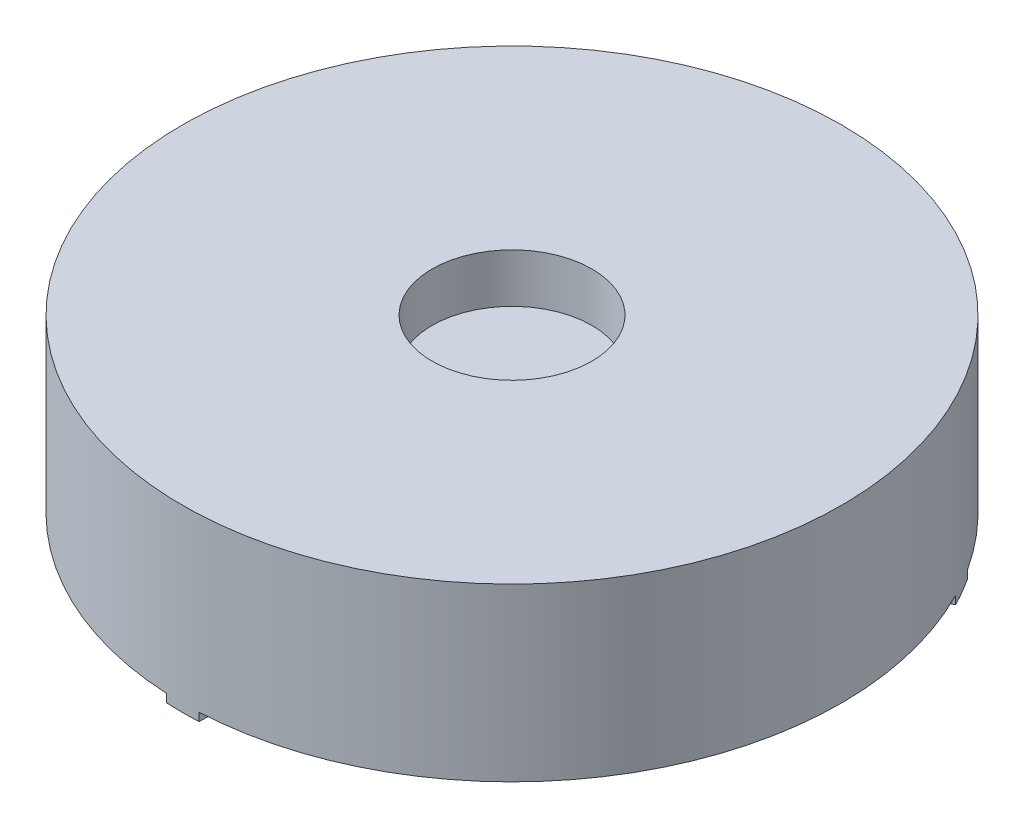
SolidWorks part; units mm, degrees
ref_plane "Front Plane" through (0, 0, 0) normal (0, 0, 1) x (1, 0, 0)
ref_plane "Top Plane" through (0, 0, 0) normal (0, 1, 0) x (1, 0, 0)
ref_plane "Right Plane" through (0, 0, 0) normal (1, 0, 0) x (0, 0, -1)
sketch "Sketch1" plane through (0, 0, 0) normal (1, 0, 0) x (0, 0, -1)
  line L2 (20.2, 10.5) -> (20.2, 0)
  line L3 (20.2, 0) -> (0, 0)
  line L4 (0, 0) -> (0, 7.5)
  line L5 (0, 7.5) -> (4.9, 7.5)
  line L6 (4.9, 7.5) -> (4.9, 10.5)
  line L7 (4.9, 10.5) -> (20.2, 10.5)
  dimension "D1" = 20.2
  dimension "D2" = 10.5
  dimension "D3" = 4.9
  dimension "D4" = 3
revolve "Revolve1" add sketch "Sketch1" angle 360 about L4
sketch "Sketch2" plane through (0, 0, 0) normal (0, -1, 0) x (1, 0, 0)
  line L0 (-1, 20.1752) -> (-1, 19.1739)
  line L1 (1, 20.1752) -> (1, 19.1739)
  line L2 (17.9723, -9.2216) -> (17.1051, -8.7209)
  line L3 (16.9723, -10.9536) -> (16.1051, -10.453)
  line L4 (-16.9723, -10.9536) -> (-16.1051, -10.453)
  line L5 (-17.9723, -9.2216) -> (-17.1051, -8.7209)
  arc A0 (1, 19.1739) -> (-1, 19.1739) centre (0, 0) ccw
  circle A1 centre (0, 0) radius 20.2
  arc A2 (1, 20.1752) -> (-1, 20.1752) centre (0, 0) ccw
  circle A3 centre (0, 0) radius 20.2 construction
  arc A4 (16.9723, -10.9536) -> (17.9723, -9.2216) centre (0, 0) ccw
  arc A5 (16.1051, -10.453) -> (17.1051, -8.7209) centre (0, 0) ccw
  arc A6 (-17.9723, -9.2216) -> (-16.9723, -10.9536) centre (0, 0) ccw
  arc A7 (-17.1051, -8.7209) -> (-16.1051, -10.453) centre (0, 0) ccw
  point P0 (0, 20.2)
  point P20 (0, 0)
  dimension "D2" = 1
  dimension "D3" = 2
  dimension "D1" = 0
  dimension "D4" = 3
extrude "Boss-Extrude1" add sketch "Sketch2" along normal blind 0.5
sketch "Sketch3" plane through (0, 0, 0) normal (0, -1, 0) x (1, 0, 0)
  line L0 (0, 0) -> (0, -14.5) construction
  line L1 (0, 0) -> (0, 4) construction
  circle A0 centre (0, 4) radius 0.5
  circle A1 centre (0, -14.5) radius 0.5
  dimension "D1" = 1
  dimension "D2" = 4
  dimension "D3" = 14.5
extrude "Boss-Extrude2" add sketch "Sketch3" along normal blind 3.1
